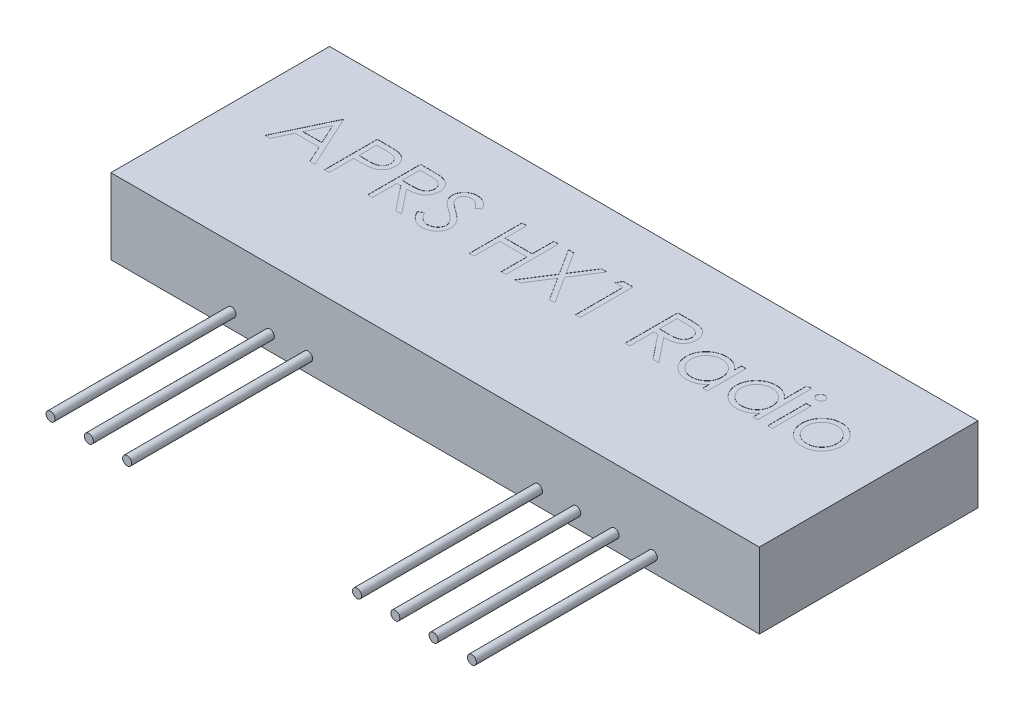
SolidWorks part; units mm, degrees
ref_plane "Front Plane" through (0, 0, 0) normal (0, 0, 1) x (1, 0, 0)
ref_plane "Top Plane" through (0, 0, 0) normal (0, 1, 0) x (1, 0, 0)
ref_plane "Right Plane" through (0, 0, 0) normal (1, 0, 0) x (0, 0, -1)
sketch "Sketch2" plane through (0, 0, 0) normal (0, 1, 0) x (1, 0, 0)
  line L1 (-21.5, -7.25) -> (21.5, -7.25)
  line L2 (-21.5, -7.25) -> (-21.5, 7.25)
  line L3 (-21.5, 7.25) -> (21.5, 7.25)
  line L4 (21.5, -7.25) -> (21.5, 7.25)
  line L5 (-21.5, -7.25) -> (21.5, 7.25) construction
  line L6 (-21.5, 7.25) -> (21.5, -7.25) construction
  point P0 (0, 0)
  dimension "D1" = 14.5
  dimension "D2" = 43
extrude "Boss-Extrude1" add sketch "Sketch2" along normal blind 5
sketch "Sketch3" plane through (0, 0, 7.25) normal (0, 0, 1) x (1, 0, 0)
  line L0 (-21.5, 1) -> (21.5, 1) construction
  line L1 (-21.5, 5) -> (-21.5, 0) construction
  line L2 (21.5, 5) -> (21.5, 0) construction
  line L3 (-21.5, 0) -> (21.5, 0) construction
  circle A0 centre (6.82, 1) radius 0.3
  circle A1 centre (9.36, 1) radius 0.3
  circle A2 centre (11.9, 1) radius 0.3
  circle A3 centre (14.44, 1) radius 0.3
  circle A4 centre (-8.42, 1) radius 0.3
  circle A5 centre (-10.96, 1) radius 0.3
  circle A6 centre (-13.5, 1) radius 0.3
  dimension "D1" = 0.6
  dimension "D3" = 2.54
  dimension "D4" = 2.54
  dimension "D5" = 15.24
  dimension "D6" = 2.54
  dimension "D7" = 1
  dimension "D8" = 8
  dimension "D2" = 4
extrude "Boss-Extrude2" add sketch "Sketch3" along normal blind 12
sketch "Sketch4" plane through (0, 5, 0) normal (0, 1, 0) x (1, 0, 0)
  line L0 (-21.5, 0) -> (21.5, 0) construction
  line L1 (-21.5, 7.25) -> (-21.5, -7.25) construction
  line L2 (21.5, -7.25) -> (21.5, 7.25) construction
  text T0 "APRS HX1 Radio"
extrude "Cut-Extrude1" cut sketch "Sketch4" against normal blind 0.01
